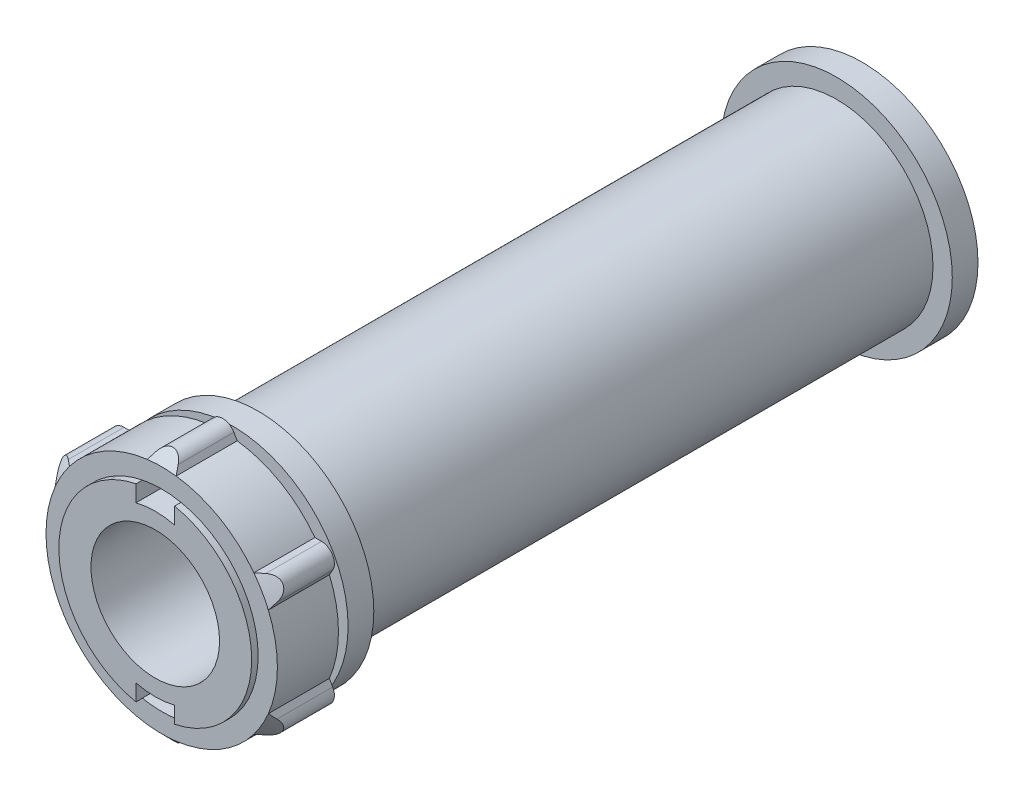
SolidWorks part; units mm, degrees
ref_plane "Front" through (0, 0, 0) normal (0, 0, 1) x (1, 0, 0)
ref_plane "Top" through (0, 0, 0) normal (0, 1, 0) x (1, 0, 0)
ref_plane "Right" through (0, 0, 0) normal (1, 0, 0) x (0, 0, -1)
sketch "Sketch1" plane through (0, 0, 0) normal (0, 0, 1) x (1, 0, 0)
  circle A0 centre (0, 0) radius 15
  circle A1 centre (0, 0) radius 13.25
  dimension "D1" = 30
  dimension "D2" = 26.5
extrude "Boss-Extrude1" add sketch "Sketch1" along normal blind 110
sketch "Sketch2" plane through (0, 0, 0) normal (0, 0, 1) x (1, 0, 0)
  circle A0 centre (0, 0) radius 18
  circle A1 centre (0, 0) radius 15 construction
  circle A2 centre (0, 0) radius 15
  dimension "D1" = 36
extrude "Boss-Extrude2" add sketch "Sketch2" along normal blind 4
sketch "Sketch3" plane through (0, 0, 0) normal (0, 0, 1) x (1, 0, 0)
  circle A0 centre (0, 0) radius 18 construction
  circle A1 centre (0, 0) radius 18
  circle A2 centre (0, 0) radius 15 construction
  circle A3 centre (0, 0) radius 15
extrude "Boss-Extrude3" add sketch "Sketch3" along normal blind 4 from offset 94
sketch "Sketch4" plane through (0, 0, 110) normal (0, 0, 1) x (1, 0, 0)
  circle A0 centre (0, 0) radius 13.25 construction
  circle A1 centre (0, 0) radius 13.25
  circle A2 centre (0, 0) radius 10
  dimension "D1" = 20
extrude "Boss-Extrude4" add sketch "Sketch4" against normal blind 24
sketch "Sketch6" plane through (0, 0, 110) normal (0, 0, 1) x (1, 0, 0)
  line L0 (-3, 14.6969) -> (-3, 12.1347)
  line L1 (0, 18) -> (0, 0) construction
  line L2 (0, 0) -> (18, 0) construction
  line L3 (3, 14.6969) -> (3, 12.1347)
  line L4 (3, -14.6969) -> (3, -12.1347)
  line L5 (-3, -14.6969) -> (-3, -12.1347)
  circle A0 centre (0, 0) radius 15 construction
  arc A1 (3, 14.6969) -> (-3, 14.6969) centre (0, 0) ccw
  arc A2 (3, 12.1347) -> (-3, 12.1347) centre (0, 0) ccw
  circle A3 centre (0, 0) radius 18 construction
  arc A4 (3, -12.1347) -> (-3, -12.1347) centre (0, 0) cw
  arc A5 (3, -14.6969) -> (-3, -14.6969) centre (0, 0) cw
  dimension "D1" = 6
  dimension "25/2" = 12.5
extrude "Cut-Extrude1" cut sketch "Sketch6" against normal blind 7
sketch "Sketch7" plane through (0, 0, 103) normal (0, 0, 1) x (1, 0, 0)
  line L0 (0, 12.5) -> (0, 0) construction
  line L1 (3, 14.6969) -> (3, 12.1347)
  line L2 (7, -10.3562) -> (7, -13.2665)
  line L3 (-3, -14.6969) -> (-3, -12.1347)
  line L4 (-7, 10.3562) -> (-7, 13.2665)
  line L5 (-3, -12.1347) -> (-3, -14.6969) construction
  line L6 (3, -14.6969) -> (3, -12.1347) construction
  arc A0 (3, 12.1347) -> (-3, 12.1347) centre (0, 0) ccw construction
  arc A1 (7, -10.3562) -> (3, 12.1347) centre (0, 0) ccw
  arc A2 (7, -13.2665) -> (3, 14.6969) centre (0, 0) ccw
  arc A3 (-3, 14.6969) -> (-3, -14.6969) centre (0, 0) ccw construction
  arc A4 (-7, 13.2665) -> (-3, -14.6969) centre (0, 0) ccw
  arc A5 (-7, 10.3562) -> (-3, -12.1347) centre (0, 0) ccw
  point P22 (0, 0)
  dimension "D1" = 2
  dimension "D2" = 4
extrude "Cut-Extrude2" cut sketch "Sketch7" along normal blind 4
sketch "Sketch5" plane through (0, 0, 98) normal (0, 0, 1) x (1, 0, 0)
  circle A0 centre (0, 0) radius 18
  circle A1 centre (0, 0) radius 18 construction
  circle A2 centre (0, 0) radius 15
  dimension "D1" = 30
extrude "Boss-Extrude5" add sketch "Sketch5" along normal blind 9.5 from offset 1.5 separate body
sketch "Sketch8" plane through (0, 0, 99.5) normal (0, 0, -1) x (-1, 0, 0)
  line L0 (-2.25, 17.8588) -> (-1.7372, 18.747)
  line L1 (1.7372, 18.747) -> (2.25, 17.8588)
  line L2 (0, 17.7441) -> (0, 0) construction
  line L3 (14.3412, 10.878) -> (15.3668, 10.878)
  line L4 (17.104, 7.8691) -> (16.5912, 6.9809)
  line L5 (16.5912, -6.9809) -> (17.104, -7.8691)
  line L6 (15.3668, -10.878) -> (14.3412, -10.878)
  line L7 (2.25, -17.8588) -> (1.7372, -18.747)
  line L8 (-1.7372, -18.747) -> (-2.25, -17.8588)
  line L9 (-14.3412, -10.878) -> (-15.3668, -10.878)
  line L10 (-17.104, -7.8691) -> (-16.5912, -6.9809)
  line L11 (-16.5912, 6.9809) -> (-17.104, 7.8691)
  line L12 (-15.3668, 10.878) -> (-14.3412, 10.878)
  circle A0 centre (0, 0) radius 18 construction
  arc A1 (2.25, 17.8588) -> (-2.25, 17.8588) centre (0, 0) ccw
  arc A2 (-1.7372, 18.747) -> (1.7372, 18.747) centre (0, 17.7441) cw
  arc A3 (16.5912, 6.9809) -> (14.3412, 10.878) centre (0, 0) ccw
  arc A4 (15.3668, 10.878) -> (17.104, 7.8691) centre (15.3668, 8.872) cw
  arc A5 (14.3412, -10.878) -> (16.5912, -6.9809) centre (0, 0) ccw
  arc A6 (17.104, -7.8691) -> (15.3668, -10.878) centre (15.3668, -8.872) cw
  arc A7 (-2.25, -17.8588) -> (2.25, -17.8588) centre (0, 0) ccw
  arc A8 (1.7372, -18.747) -> (-1.7372, -18.747) centre (0, -17.7441) cw
  arc A9 (-16.5912, -6.9809) -> (-14.3412, -10.878) centre (0, 0) ccw
  arc A10 (-15.3668, -10.878) -> (-17.104, -7.8691) centre (-15.3668, -8.872) cw
  arc A11 (-14.3412, 10.878) -> (-16.5912, 6.9809) centre (0, 0) ccw
  arc A12 (-17.104, 7.8691) -> (-15.3668, 10.878) centre (-15.3668, 8.872) cw
  point P35 (0, 0)
  dimension "D1" = 6
  dimension "D2" = 39.5
  dimension "D3" = 4.5
  dimension "D4" = 60
extrude "Boss-Extrude6" add sketch "Sketch8" against normal up to surface (9.5 mm away) up to face at (18, 0, 109)
sketch "Sketch10" plane through (0, 0, 0) normal (1, 0, 0) x (0, 0, -1)
  line L0 (-109, 19.75) -> (-109, 18)
  line L1 (-109, 17.8588) -> (-109, 10.878) construction
  line L2 (-109, 18) -> (-107.25, 19.75)
  line L3 (-99.5, 19.75) -> (-109, 19.75) construction
  line L4 (-107.25, 19.75) -> (-109, 19.75)
  line L5 (-109, 0) -> (-99.5, 0) construction
  line L6 (-109, 6.9809) -> (-109, -6.9809) construction
  line L7 (-99.5, -6.9809) -> (-99.5, 6.9809) construction
  dimension "D1" = 18
revolve "Cut-Revolve1" cut sketch "Sketch10" angle 360 about L5
